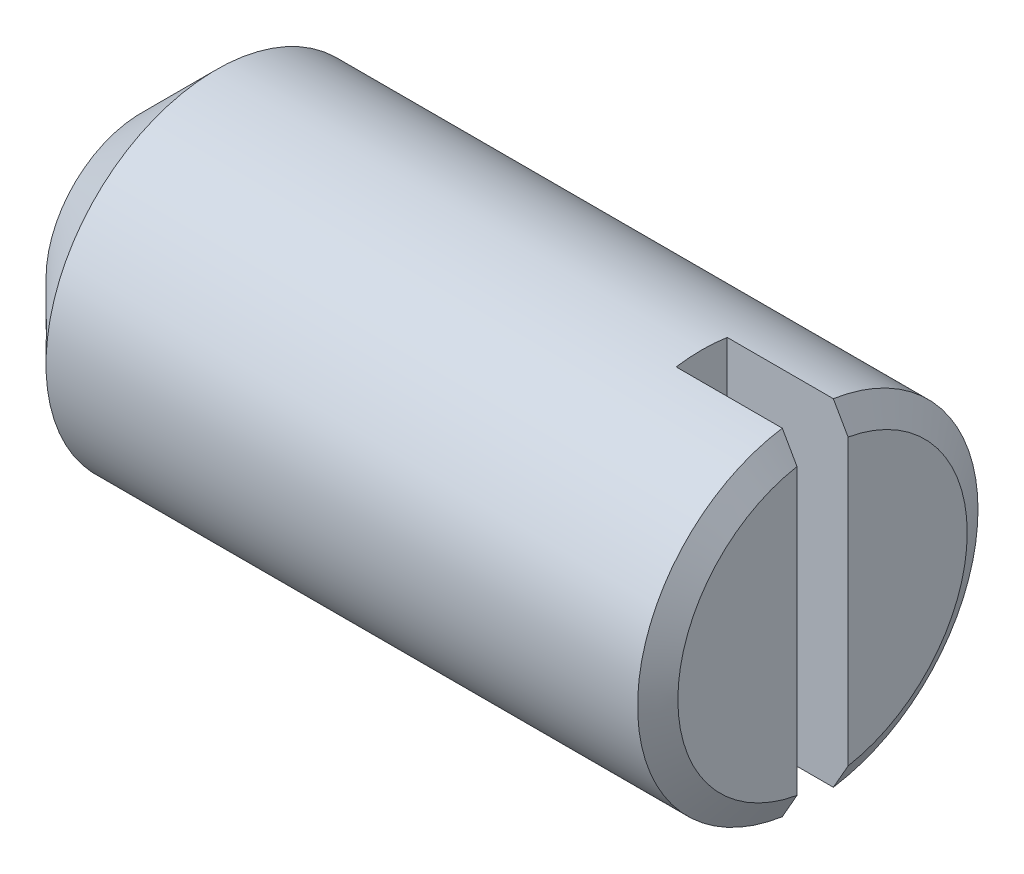
SolidWorks part; units mm, degrees
ref_plane "Přední rovina" through (0, 0, 0) normal (0, 0, 1) x (1, 0, 0)
ref_plane "Vrchní rovina" through (0, 0, 0) normal (0, 1, 0) x (1, 0, 0)
ref_plane "Pravá rovina" through (0, 0, 0) normal (1, 0, 0) x (0, 0, -1)
sketch "Skica1" plane through (0, 0, 0) normal (0, 1, 0) x (1, 0, 0)
  line L0 (0, 0) -> (0, 1.125)
  line L1 (0, 1.125) -> (0.875, 2)
  line L2 (0.875, 2) -> (7.8268, 2)
  line L3 (7.8268, 2) -> (8, 1.7)
  line L4 (8, 1.7) -> (8, 0)
  line L5 (8, 0) -> (0, 0) construction
  line L6 (0, 0) -> (8, 0)
  dimension "D1" = 45
  dimension "l" = 8
  dimension "M" = 4
  dimension "D4" = 3.4
  dimension "ALFA/2" = 60
  dimension "dt" = 2.25
revolve "Otočit kolem osy1" add sketch "Skica1" angle 360 about L5
cosmetic thread "Kosmetický závit1" parameters "D2"=0.9
sketch "Skica2" plane through (8, 0, 0) normal (1, 0, 0) x (0, 0, -1)
  line L0 (0, 2) -> (0, 0) construction
  line L1 (-0.3, 2) -> (0.3, 2)
  line L2 (-0.3, 2) -> (-0.3, -2)
  line L3 (-0.3, -2) -> (0.3, -2)
  line L4 (0.3, 2) -> (0.3, -2)
  line L5 (0, 0) -> (0.3, 0) construction
  circle A0 centre (0, 0) radius 2 construction
  dimension "n" = 0.6
extrude "Odebrat vysunutím1" cut sketch "Skica2" against normal blind 1.42
equation "\"D4@Skica1\" = \"M@Skica1\" * 0.85"
